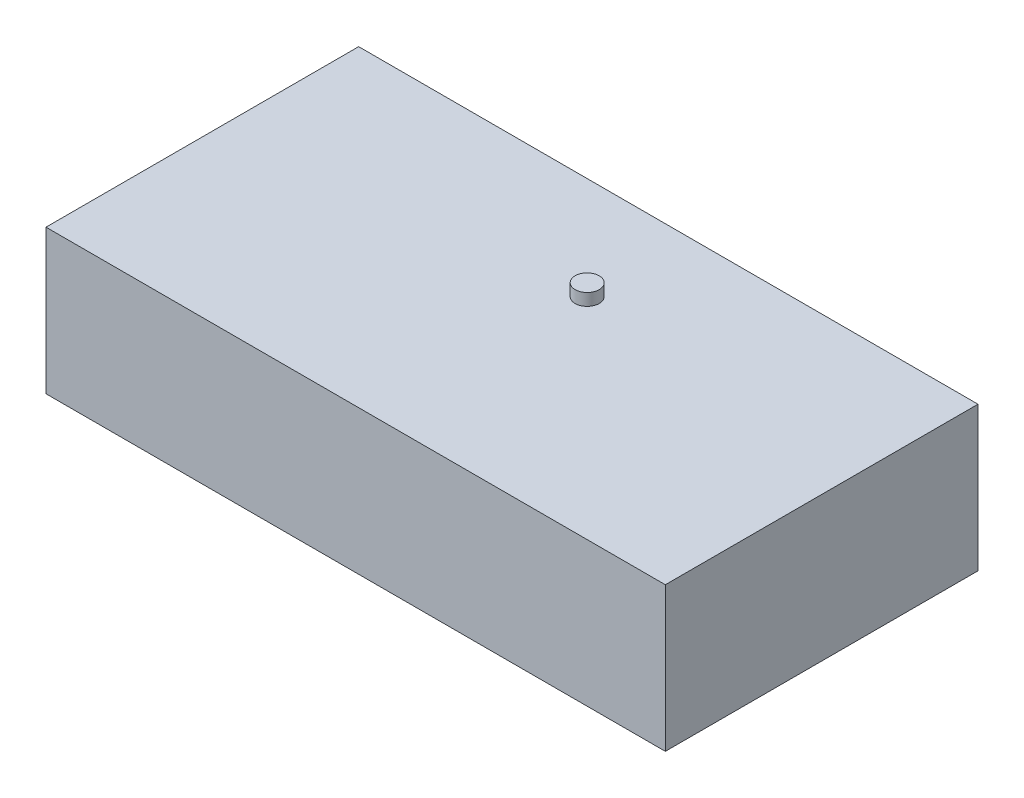
SolidWorks part; units mm, degrees
ref_plane "Front Plane" through (0, 0, 0) normal (0, 0, 1) x (1, 0, 0)
ref_plane "Top Plane" through (0, 0, 0) normal (0, 1, 0) x (1, 0, 0)
ref_plane "Right Plane" through (0, 0, 0) normal (1, 0, 0) x (0, 0, -1)
sketch "Sketch1" plane through (0, 0, 0) normal (0, 1, 0) x (1, 0, 0)
  line L1 (0, 0) -> (51.5, 0)
  line L2 (0, 0) -> (0, 26)
  line L3 (0, 26) -> (51.5, 26)
  line L4 (51.5, 0) -> (51.5, 26)
  dimension "D1" = 26
  dimension "D2" = 51.5
extrude "Boss-Extrude1" add sketch "Sketch1" along normal blind 12
sketch "Sketch2" plane through (0, 12, 0) normal (0, 1, 0) x (1, 0, 0)
  line L0 (51.5, 0) -> (51.5, 26) construction
  line L1 (51.5, 26) -> (0, 26) construction
  circle A0 centre (27.5, 17.5) radius 1
  dimension "D3" = 2
  dimension "D1" = 25
  dimension "D2" = 9.5
extrude "Boss-Extrude2" add sketch "Sketch2" along normal blind 1
